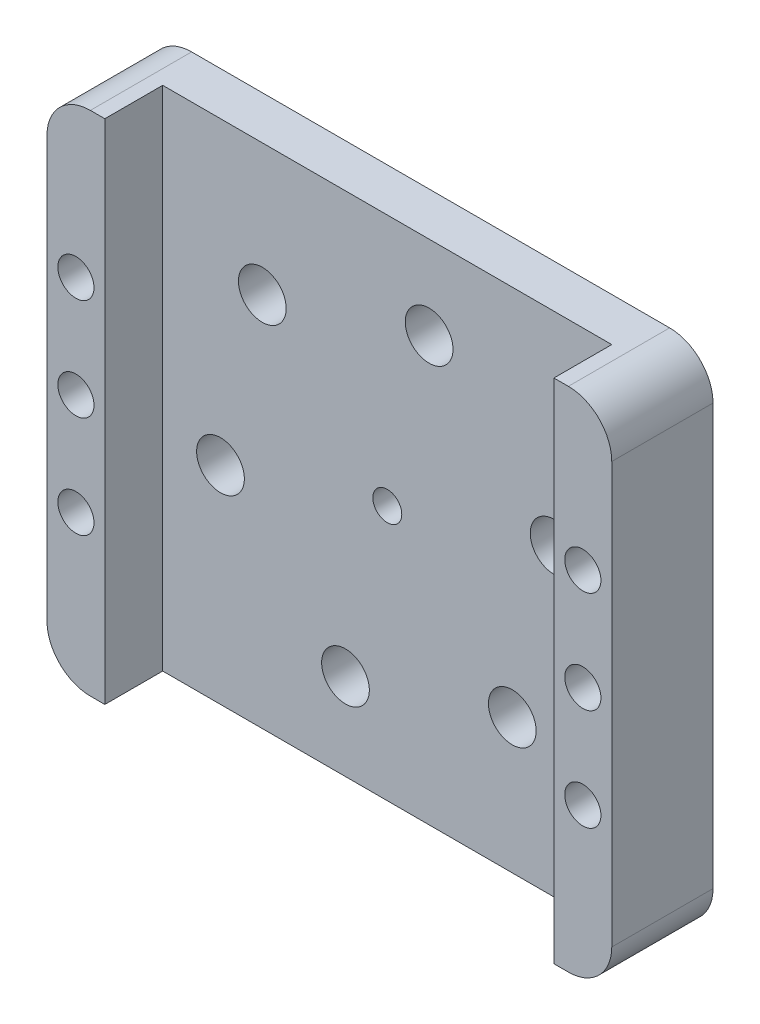
SolidWorks part; units mm, degrees
ref_plane "前视基准面" through (0, 0, 0) normal (0, 0, 1) x (1, 0, 0)
ref_plane "上视基准面" through (0, 0, 0) normal (0, 1, 0) x (1, 0, 0)
ref_plane "右视基准面" through (0, 0, 0) normal (1, 0, 0) x (0, 0, -1)
other "Configuration Table"
sketch "草图3" plane through (0, 0, 0) normal (0, 0, 1) x (1, 0, 0)
  line L0 (-72.611, 57.5893) -> (-73.611, 57.5893)
  line L5 (-72.611, 57.5893) -> (-35.5658, 57.5893)
  line L7 (-72.611, 22.5185) -> (-35.5658, 22.5185)
  line L9 (-72.611, 57.5893) -> (-35.5658, 22.5185) construction
  line L10 (-72.611, 22.5185) -> (-35.5658, 57.5893) construction
  line L11 (-35.5658, 22.5185) -> (-34.5658, 22.5185)
  line L12 (-35.5658, 57.5893) -> (-34.5658, 57.5893)
  line L13 (-34.5658, 57.5893) -> (-34.5658, 22.5185)
  line L14 (-73.611, 57.5893) -> (-73.611, 22.5185)
  line L15 (-73.611, 22.5185) -> (-72.611, 22.5185)
  circle A1 centre (-51.1928, 51.8102) radius 1.65
  circle A2 centre (-42.552, 43.4833) radius 1.65
  circle A3 centre (-45.4429, 31.8367) radius 1.65
  circle A4 centre (-56.9746, 28.517) radius 1.65
  circle A5 centre (-65.6154, 36.8439) radius 1.65
  circle A6 centre (-62.7245, 48.4905) radius 1.65
  circle A7 centre (-54.0884, 40.0539) radius 27
  point P0 (-54.0837, 40.1636)
extrude "凸台-拉伸2" add sketch "草图3" along normal blind 3
sketch "草图4" plane through (0, 0, 3) normal (0, 0, 1) x (1, 0, 0)
  line L4 (-73.611, 57.5893) -> (-34.5658, 57.5893) construction
  line L11 (-69.611, 57.5893) -> (-69.611, 22.5185)
  line L13 (-38.5658, 57.5893) -> (-38.5658, 22.5185)
  line L15 (-73.611, 22.5185) -> (-73.611, 57.5893)
  line L19 (-73.611, 57.5893) -> (-69.611, 57.5893)
  line L20 (-73.611, 22.5185) -> (-69.611, 22.5185)
  line L21 (-38.5658, 22.5185) -> (-34.5658, 22.5185)
  line L22 (-34.5658, 22.5185) -> (-34.5658, 57.5893)
  line L23 (-34.5658, 57.5893) -> (-38.5658, 57.5893)
  circle A12 centre (-71.611, 47.0893) radius 1.25
  circle A13 centre (-71.611, 33.0185) radius 1.25
  circle A14 centre (-71.611, 40.0539) radius 1.25
  circle A15 centre (-36.5658, 47.0893) radius 1.25
  circle A18 centre (-36.5658, 40.0539) radius 1.25
  circle A19 centre (-36.5658, 33.0185) radius 1.25
extrude "凸台-拉伸3" add sketch "草图4" along normal blind 4
sketch "草图5" plane through (0, 0, 3) normal (0, 0, 1) x (1, 0, 0)
  line L0 (-51.1928, 51.8102) -> (-56.9746, 28.517) construction
  circle A1 centre (-54.0837, 40.1636) radius 1
  circle A2 centre (-71.611, 47.0893) radius 1.25
  circle A3 centre (-71.611, 40.0539) radius 1.25
  circle A4 centre (-71.611, 33.0185) radius 1.25
  circle A5 centre (-36.5658, 47.0893) radius 1.25
  circle A6 centre (-36.5658, 40.0539) radius 1.25
  circle A7 centre (-36.5658, 33.0185) radius 1.25
extrude "切除-拉伸1" cut sketch "草图5" against normal blind 10
fillet "圆角1" radius 3 1 edges at (-73.611, 22.5185, 3.5)
fillet "圆角2" radius 3 1 edges at (-73.611, 57.5893, 3.5)
fillet "圆角3" radius 3 1 edges at (-34.5658, 57.5893, 3.5)
fillet "圆角4" radius 3 1 edges at (-34.5658, 22.5185, 3.5)
